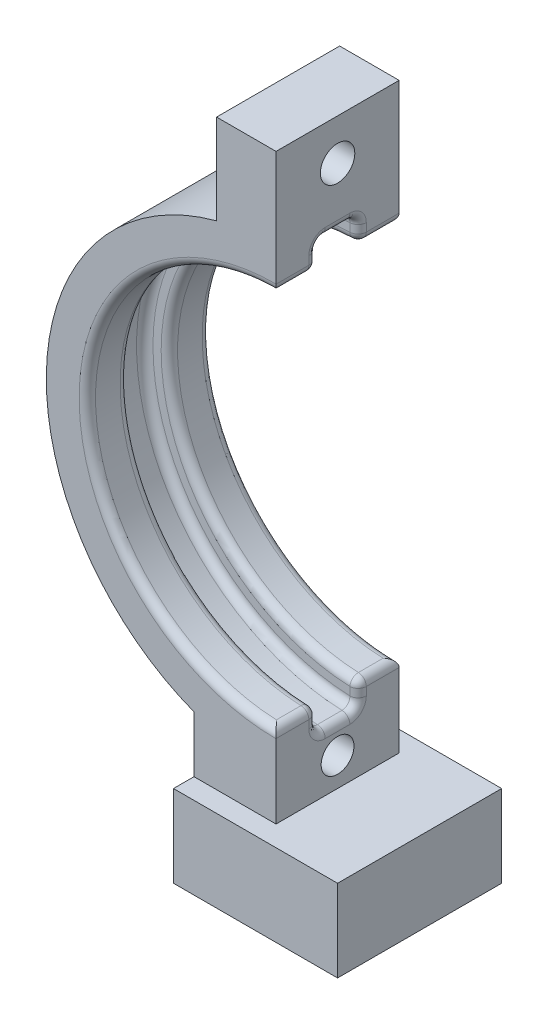
SolidWorks part; units mm, degrees
ref_plane "Front Plane" through (0, 0, 0) normal (0, 0, 1) x (1, 0, 0)
ref_plane "Top Plane" through (0, 0, 0) normal (0, 1, 0) x (1, 0, 0)
ref_plane "Right Plane" through (0, 0, 0) normal (1, 0, 0) x (0, 0, -1)
ref_plane "Base Plane " through (0, 0, 0) normal (0, 1, 0) x (1, 0, 0)
sketch "Sketch1" plane through (0, 0, 0) normal (0, 1, 0) x (1, 0, 0)
  line L1 (0, 0) -> (20, 0)
  line L2 (0, 0) -> (0, -40)
  line L3 (0, -40) -> (20, -40)
  line L4 (20, 0) -> (20, -40)
  dimension "D1" = 20
  dimension "D2" = 40
extrude "Boss-Extrude1" add sketch "Sketch1" along normal blind 15
ref_plane "Top of slider" through (0, 15, 0) normal (0, 1, 0) x (1, 0, 0)
sketch "Sketch2" plane through (0, 15, 0) normal (0, 1, 0) x (1, 0, 0)
  line L0 (0, 0) -> (0, -40) construction
  line L1 (0, -10) -> (20, -10)
  line L2 (0, -10) -> (0, -30)
  line L3 (0, -30) -> (20, -30)
  line L4 (20, -10) -> (20, -30)
  line L5 (20, -40) -> (20, 0) construction
  line L6 (20, 0) -> (0, 0) construction
  dimension "D1" = 20
  dimension "D2" = 10
extrude "Boss-Extrude2" add sketch "Sketch2" along normal blind 10
ref_plane "Plane3" through (0, 0, 27.5) normal (0, 0, 1) x (1, 0, 0)
sketch "Sketch3" plane through (0, 0, 27.5) normal (0, 0, 1) x (1, 0, 0)
  line L0 (10, 25) -> (10, 57.4901) construction
  line L1 (0, 25) -> (20, 25) construction
  line L2 (10, 35) -> (10, 25)
  line L3 (10, 25) -> (0, 25)
  line L4 (0, 25) -> (0, 83.173) construction
  line L5 (0, 31.8466) -> (0, 25)
  line L6 (10, 86) -> (10, 81)
  arc A0 (10, 35) -> (10, 81) centre (10, 58) cw
  arc A1 (10, 86) -> (0, 31.8466) centre (10, 58) ccw
  dimension "D1" = 23
  dimension "D3" = 28
  dimension "D2" = 10
extrude "Boss-Extrude3" add sketch "Sketch3" against normal blind 5
ref_plane "Plane4" through (0, 0, 22.5) normal (0, 0, -1) x (-1, 0, 0)
sketch "Sketch4" plane through (0, 0, 22.5) normal (0, 0, -1) x (-1, 0, 0)
  line L0 (-10, 25) -> (-10, 35) construction
  line L1 (-10, 86) -> (-10, 84)
  line L2 (-10, 81) -> (-10, 86) construction
  line L3 (-10, 30) -> (-10, 32)
  line L4 (0, 31.8466) -> (0, 25)
  line L5 (0, 25) -> (-10, 25)
  line L6 (-20, 25) -> (0, 25) construction
  line L7 (-10, 25) -> (-10, 30)
  arc A0 (-10, 86) -> (0, 31.8466) centre (-10, 58) cw
  arc A1 (-10, 84) -> (-10, 32) centre (-10, 58) cw
  dimension "D3" = 26
  dimension "D4" = 28
  dimension "D1" = 2
  dimension "D2" = 2
extrude "Boss-Extrude4" add sketch "Sketch4" along normal blind 5
ref_plane "Plane5" through (0, 0, 17.5) normal (0, 0, -1) x (-1, 0, 0)
sketch "Sketch5" plane through (0, 0, 17.5) normal (0, 0, -1) x (-1, 0, 0)
  line L0 (-10, 32) -> (-10, 25) construction
  line L1 (-10, 32) -> (-10, 35) construction
  line L2 (-10, 86) -> (-10, 81)
  line L3 (-10, 35) -> (-10, 30)
  line L4 (0, 31.8466) -> (0, 25)
  line L5 (0, 25) -> (-10, 25)
  line L6 (-10, 25) -> (-10, 30)
  arc A0 (-10, 86) -> (0, 31.8466) centre (-10, 58) cw
  arc A1 (0, 31.8466) -> (-10, 86) centre (-10, 58) ccw construction
  arc A2 (-10, 30) -> (0, 31.8466) centre (-10, 58) ccw construction
  arc A3 (-10, 81) -> (-10, 35) centre (-10, 58) cw
  dimension "D1" = 28
extrude "Boss-Extrude5" add sketch "Sketch5" along normal blind 5
sketch "Sketch6" plane through (0, 0, 27.5) normal (0, 0, 1) x (1, 0, 0)
  line L0 (10, 81) -> (10, 86) construction
  line L1 (10, 86) -> (10, 96)
  line L2 (10, 96) -> (2.7531, 96)
  line L3 (2.7531, 96) -> (2.7531, 85.0459)
  arc A0 (10, 86) -> (2.7531, 85.0459) centre (10, 58) ccw
  arc A1 (10, 86) -> (0, 31.8466) centre (10, 58) ccw construction
  dimension "D1" = 28
  dimension "D2" = 15
  dimension "D3" = 90
  dimension "D4" = 10
extrude "Boss-Extrude6" add sketch "Sketch6" against normal blind 15
ref_plane "Plane6" through (10, 0, 0) normal (1, 0, 0) x (0, 0, -1)
sketch "Sketch7" plane through (10, 0, 0) normal (1, 0, 0) x (0, 0, -1)
  line L0 (-12.5, 96) -> (-27.5, 96) construction
  line L1 (-12.5, 96) -> (-12.5, 81) construction
  line L2 (-17.5, 32) -> (-22.5, 32) construction
  line L3 (-12.5, 35) -> (-12.5, 25) construction
  circle A0 centre (-20, 91) radius 2.1
  circle A1 centre (-20, 28.5) radius 2
  dimension "D1" = 4.2
  dimension "D4" = 4
  dimension "D2" = 5
  dimension "D3" = 7.5
  dimension "D5" = 3.5
  dimension "D6" = 7.5
extrude "Cut-Extrude1" cut sketch "Sketch7" against normal through all
fillet "Fillet5" radius 1 16 edges at (10, 82.5, 17.5) (10, 82.5, 22.5) (10, 33.5, 22.5) (10, 33.5, 17.5) (10, 32, 20) (10, 84, 20) (-16, 58, 17.5) (-16, 58, 22.5) (-13, 58, 22.5) (10, 35, 25) (10, 81, 25) (-13, 58, 17.5) (10, 81, 15) (10, 35, 15) (-13, 58, 27.5) (-13, 58, 12.5)
ref_plane "Plane7" through (20, 0, 0) normal (1, 0, 0) x (0, 0, -1)
sketch "Sketch9" plane through (20, 0, 0) normal (1, 0, 0) x (0, 0, -1)
  line L1 (-40, 15) -> (0, 15)
  line L2 (-40, 15) -> (-40, 0)
  line L3 (-40, 0) -> (0, 0)
  line L4 (0, 15) -> (0, 0)
extrude "Cut-Extrude2" cut sketch "Sketch9" against normal blind 20
